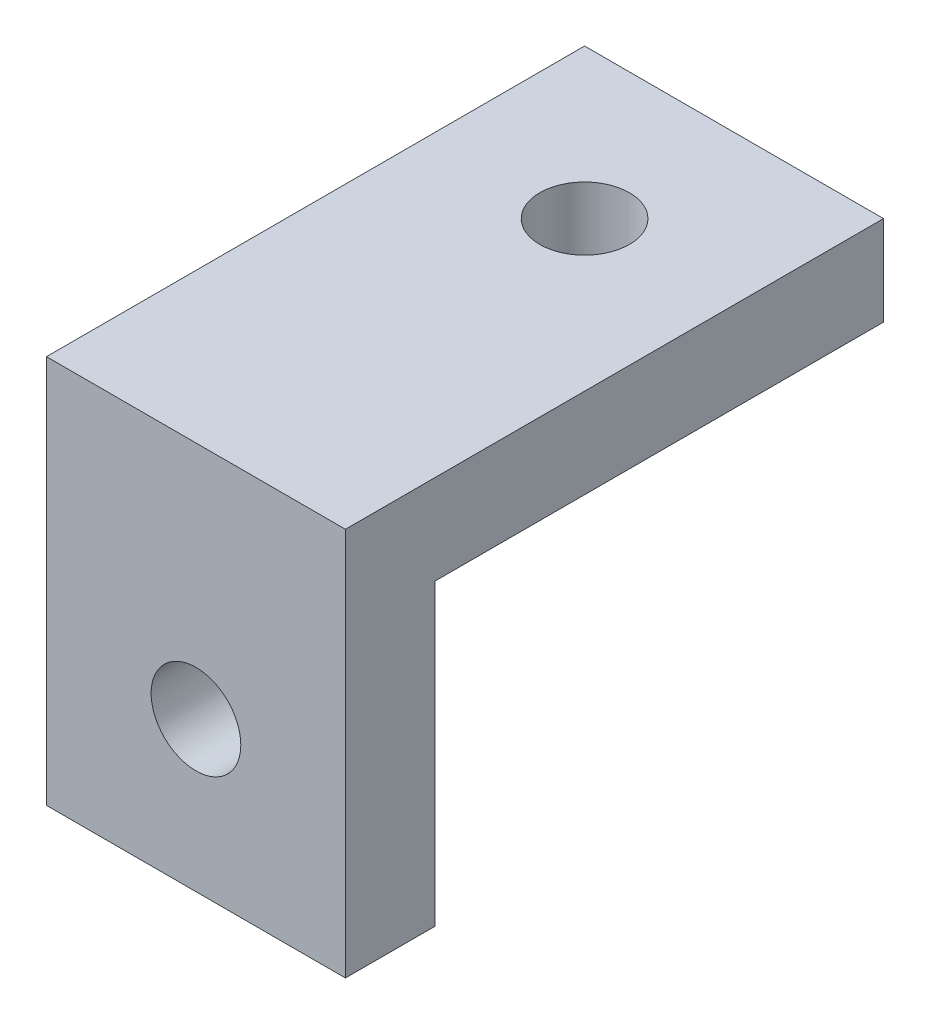
SolidWorks part; units mm, degrees
ref_plane "Front Plane" through (0, 0, 0) normal (0, 0, 1) x (1, 0, 0)
ref_plane "Top Plane" through (0, 0, 0) normal (0, 1, 0) x (1, 0, 0)
ref_plane "Right Plane" through (0, 0, 0) normal (1, 0, 0) x (0, 0, -1)
sketch "Sketch1" plane through (0, 0, 0) normal (0, 1, 0) x (1, 0, 0)
  line L0 (-55, 0) -> (55, 0) construction
  line L1 (-5, -13) -> (5, -13)
  line L2 (-5, -13) -> (-5, 5)
  line L3 (-5, 5) -> (5, 5)
  line L4 (5, -13) -> (5, 5)
  circle A0 centre (0, 0) radius 1.5
  point P0 (0, 0)
  dimension "D3" = 3
  dimension "D1" = 10
  dimension "D2" = 13
  dimension "D4" = 5
extrude "Boss-Extrude1" add sketch "Sketch1" along normal blind 3
sketch "Sketch2" plane through (0, 0, 0) normal (0, -1, 0) x (1, 0, 0)
  line L0 (5, 13) -> (5, -5) construction
  line L1 (-5, 13) -> (5, 13)
  line L2 (-5, 13) -> (-5, 10)
  line L3 (-5, 10) -> (5, 10)
  line L4 (5, 13) -> (5, 10)
  dimension "D1" = 3
extrude "Boss-Extrude2" add sketch "Sketch2" along normal blind 10
sketch "Sketch3" plane through (0, 0, 13) normal (0, 0, 1) x (1, 0, 0)
  line L0 (0, -7.15) -> (0, 7.15) construction
  line L1 (5, -10) -> (-5, -10) construction
  circle A0 centre (0, -5) radius 1.5
  dimension "D1" = 3
  dimension "D2" = 5
extrude "Cut-Extrude1" cut sketch "Sketch3" against normal through all
